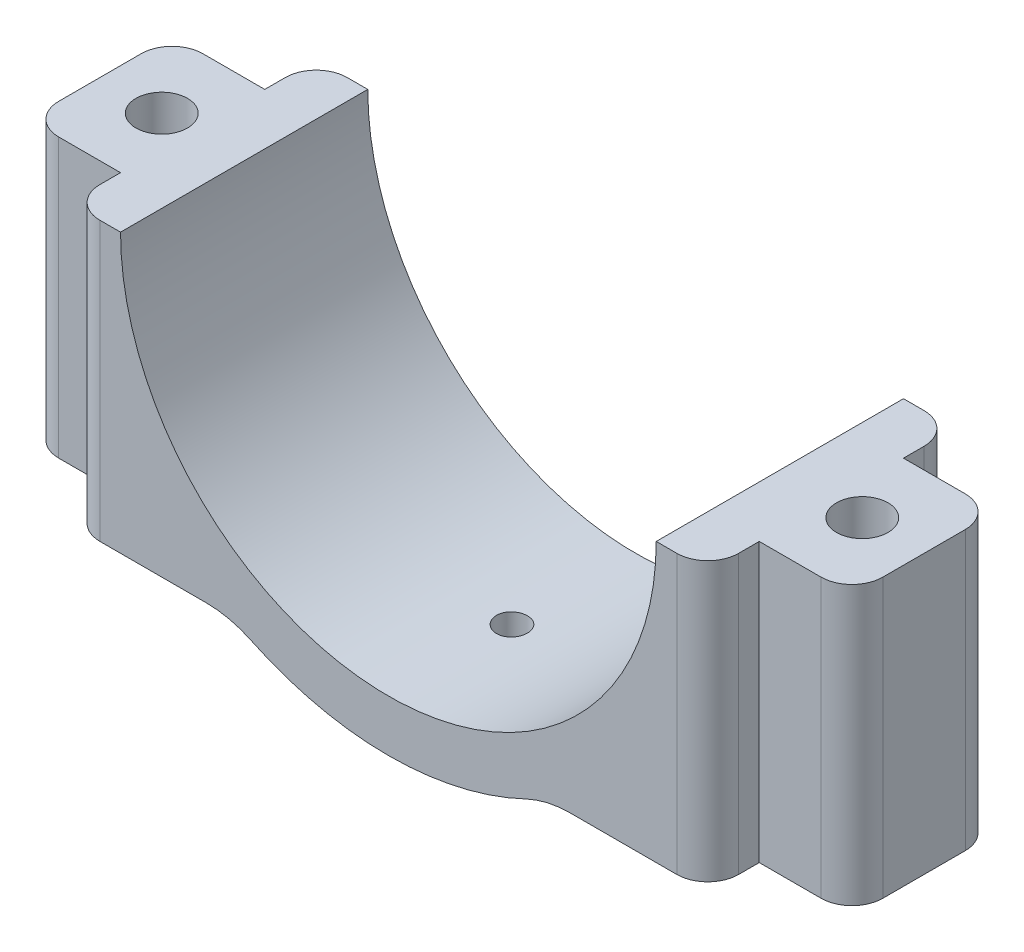
SolidWorks part; units mm, degrees
ref_plane "前视基准面" through (0, 0, 0) normal (0, 0, 1) x (1, 0, 0)
ref_plane "上视基准面" through (0, 0, 0) normal (0, 1, 0) x (1, 0, 0)
ref_plane "右视基准面" through (0, 0, 0) normal (1, 0, 0) x (0, 0, -1)
other "Configuration Table"
sketch "草图1" plane through (0, 0, 0) normal (0, 1, 0) x (1, 0, 0)
  line L1 (-40, -12) -> (40, -12)
  line L2 (-40, -12) -> (-40, 12)
  line L3 (-40, 12) -> (40, 12)
  line L4 (40, -12) -> (40, 12)
  line L5 (-40, -12) -> (40, 12) construction
  line L6 (-40, 12) -> (40, -12) construction
  point P1 (0, 0)
  dimension "D1" = 80
  dimension "D2" = 24
extrude "凸台-拉伸1" add sketch "草图1" along normal blind 27
sketch "草图2" plane through (0, 0, 12) normal (0, 0, 1) x (1, 0, 0)
  line L0 (-40, 27) -> (40, 27) construction
  line L1 (-31, 27) -> (31, 27)
  arc A0 (-31, 27) -> (31, 27) centre (0, 27) ccw
  dimension "D1" = 31
extrude "凸台-拉伸3" add sketch "草图2" against normal through all
sketch "草图3" plane through (0, 0, 12) normal (0, 0, 1) x (1, 0, 0)
  line L0 (-40, 27) -> (40, 27) construction
  line L1 (-26, 27) -> (26, 27)
  arc A0 (-26, 27) -> (26, 27) centre (0, 27) ccw
  dimension "D1" = 26
extrude "切除-拉伸1" cut sketch "草图3" against normal through all
sketch "草图4" plane through (0, 0, 0) normal (0, 1, 0) x (1, 0, 0)
  circle A0 centre (0, 0) radius 1.5
  dimension "D1" = 3
extrude "切除-拉伸3" cut sketch "草图4" against normal through all both and the other way through all
sketch "草图5" plane through (0, 0, 0) normal (0, 1, 0) x (1, 0, 0)
  line L1 (-40, 12) -> (-31, 12)
  line L2 (-40, 12) -> (-40, 7)
  line L3 (-40, 7) -> (-31, 7)
  line L4 (-31, 12) -> (-31, 7)
  dimension "D1" = 5
  dimension "D2" = 9
extrude "切除-拉伸4" cut sketch "草图5" against normal through all and the other way through all
sketch "草图6" plane through (0, 0, 0) normal (0, 1, 0) x (1, 0, 0)
  line L1 (-40, -12) -> (-31, -12)
  line L2 (-40, -12) -> (-40, -7)
  line L3 (-40, -7) -> (-31, -7)
  line L4 (-31, -12) -> (-31, -7)
  dimension "D1" = 9
  dimension "D2" = 5
extrude "切除-拉伸7" cut sketch "草图6" along normal through all
sketch "草图7" plane through (0, 0, 0) normal (0, 1, 0) x (1, 0, 0)
  line L1 (40, 12) -> (31, 12)
  line L2 (40, 12) -> (40, 7)
  line L3 (40, 7) -> (31, 7)
  line L4 (31, 12) -> (31, 7)
  dimension "D1" = 9
  dimension "D2" = 5
extrude "切除-拉伸8" cut sketch "草图7" along normal through all
sketch "草图8" plane through (0, 0, 0) normal (0, 1, 0) x (1, 0, 0)
  line L1 (40, -12) -> (31, -12)
  line L2 (40, -12) -> (40, -7)
  line L3 (40, -7) -> (31, -7)
  line L4 (31, -12) -> (31, -7)
  dimension "D1" = 5
  dimension "D2" = 9
extrude "切除-拉伸9" cut sketch "草图8" along normal through all
sketch "草图9" plane through (0, 0, 0) normal (0, 1, 0) x (1, 0, 0)
  circle A0 centre (-34, 0) radius 2.5
  dimension "D1" = 34
extrude "切除-拉伸12" cut sketch "草图9" along normal through all contours A0
sketch "草图11" plane through (0, 0, 0) normal (0, 1, 0) x (1, 0, 0)
  circle A0 centre (34, 0) radius 2.5
  dimension "D1" = 5
  dimension "D2" = 34
extrude "切除-拉伸13" cut sketch "草图11" along normal through all
fillet "圆角1" radius 3 8 edges at (31, 13.5, -12) (40, 13.5, -7) (40, 13.5, 7) (31, 13.5, 12) (-31, 13.5, 12) (-40, 13.5, 7) (-40, 13.5, -7) (-31, 13.5, -12)
fillet "圆角2" radius 10 2 edges at (15.2315, 0, 0) (-15.2315, 0, 0)
